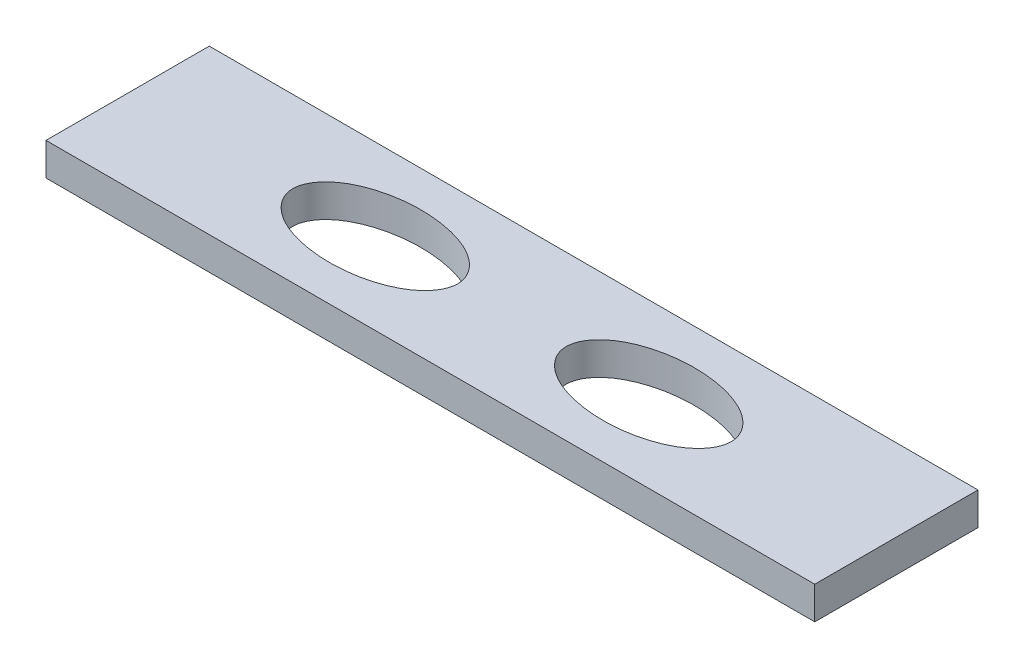
SolidWorks part; units mm, degrees
ref_plane "Front Plane" through (0, 0, 0) normal (0, 0, 1) x (1, 0, 0)
ref_plane "Top Plane" through (0, 0, 0) normal (0, 1, 0) x (1, 0, 0)
ref_plane "Right Plane" through (0, 0, 0) normal (1, 0, 0) x (0, 0, -1)
sketch "Sketch1" plane through (0, 0, 0) normal (0, 1, 0) x (1, 0, 0)
  line L1 (-36.6245, 6.7803) -> (10.4655, 6.7803)
  line L2 (-36.6245, 6.7803) -> (-36.6245, -3.2197)
  line L3 (-36.6245, -3.2197) -> (10.4655, -3.2197)
  line L4 (10.4655, 6.7803) -> (10.4655, -3.2197)
  line L5 (-36.6245, 6.7803) -> (10.4655, -3.2197) construction
  line L6 (-36.6245, -3.2197) -> (10.4655, 6.7803) construction
  line L7 (-13.0795, -3.2197) -> (-13.0795, 6.7803) construction
  line L8 (-9.7545, 1.7803) -> (0.3455, 1.7803) construction
  line L9 (-26.5045, 1.7803) -> (-16.4045, 1.7803) construction
  spline S0 degree 3 poles (-8.6425, 3.9889) (-10.3106, 1.7803) (-8.6425, -0.4283) (-4.7045, -1.3154) (-0.7666, -0.4283) (0.9015, 1.7803) (-0.7666, 3.9889) (-4.7045, 4.876) (-8.6425, 3.9889) (-10.3106, 1.7803) (-8.6425, -0.4283) knots -2.356194 -1.570796 -0.785398 0 0.785398 1.570796 2.356194 3.141593 3.926991 4.712389 5.497787 6.283185 7.068583 7.853982 8.63938 only from (-9.7545, 1.7803) to (-9.7545, 1.7803)
  spline S1 degree 3 poles (-17.5166, 3.9889) (-15.8485, 1.7803) (-17.5166, -0.4283) (-21.4545, -1.3154) (-25.3925, -0.4283) (-27.0606, 1.7803) (-25.3925, 3.9889) (-21.4545, 4.876) (-17.5166, 3.9889) (-15.8485, 1.7803) (-17.5166, -0.4283) knots -2.356194 -1.570796 -0.785398 0 0.785398 1.570796 2.356194 3.141593 3.926991 4.712389 5.497787 6.283185 7.068583 7.853982 8.63938 only from (-16.4045, 1.7803) to (-16.4045, 1.7803)
  point P0 (-13.0795, 1.7803)
  point P5 (-21.4545, 1.7803)
  point P14 (-4.7045, 1.7803)
  dimension "D3" = 16.75
  dimension "D4" = 10.1
  dimension "D1" = 10
  dimension "D2" = 47.09
  dimension "D5" = 10.1
extrude "Boss-Extrude1" add sketch "Sketch1" along normal blind 2
